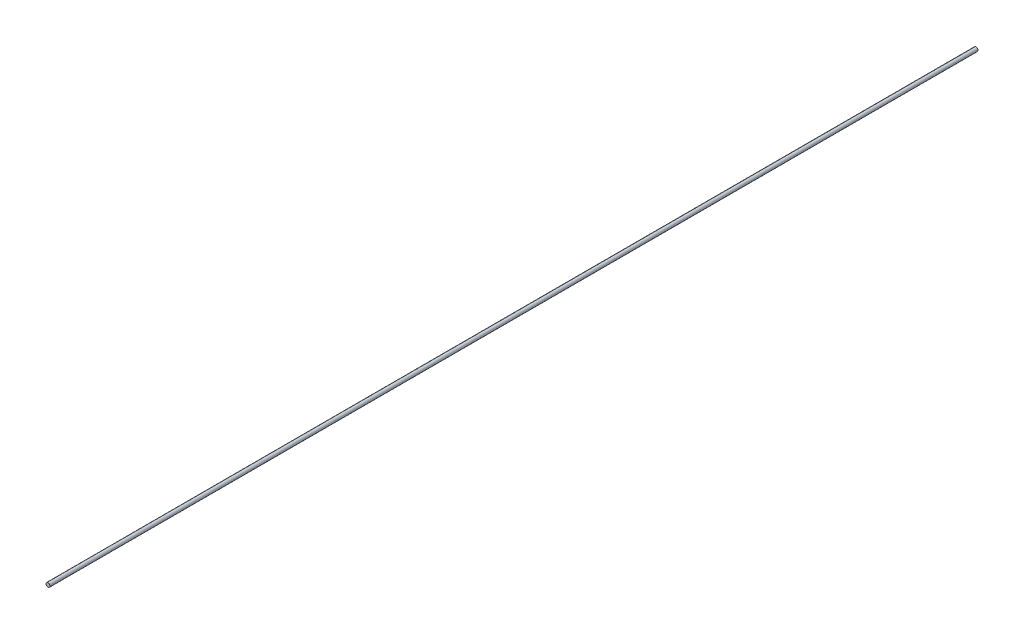
SolidWorks part; units mm, degrees
ref_plane "Front Plane" through (0, 0, 0) normal (0, 0, 1) x (1, 0, 0)
ref_plane "Top Plane" through (0, 0, 0) normal (0, 1, 0) x (1, 0, 0)
ref_plane "Right Plane" through (0, 0, 0) normal (1, 0, 0) x (0, 0, -1)
sketch "Sketch1" plane through (0, 0, 0) normal (0, 0, 1) x (1, 0, 0)
  circle A0 centre (0, 0) radius 2
  dimension "D1" = 4
extrude "Boss-Extrude1" add sketch "Sketch1" along normal blind 934.05
